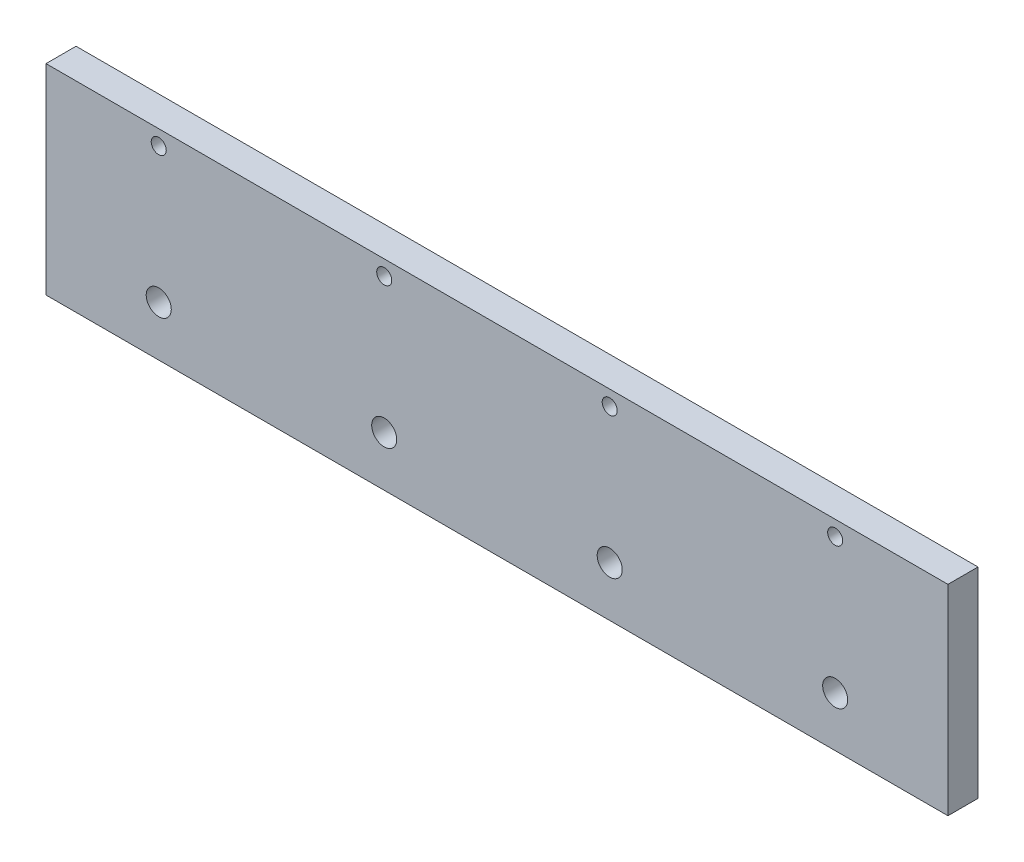
SolidWorks part; units mm, degrees
material "Beech"
ref_plane "Front Plane" through (0, 0, 0) normal (0, 0, 1) x (1, 0, 0)
ref_plane "Top Plane" through (0, 0, 0) normal (0, 1, 0) x (1, 0, 0)
ref_plane "Right Plane" through (0, 0, 0) normal (1, 0, 0) x (0, 0, -1)
sketch "Sketch1" plane through (0, 0, 0) normal (0, 0, 1) x (1, 0, 0)
  line L1 (-180, -40) -> (180, -40)
  line L2 (-180, -40) -> (-180, 40)
  line L3 (-180, 40) -> (180, 40)
  line L4 (180, -40) -> (180, 40)
  line L5 (-180, -40) -> (180, 40) construction
  line L6 (-180, 40) -> (180, -40) construction
  point P0 (0, 0)
extrude "Boss-Extrude1" add sketch "Sketch1" along normal blind 12
sketch "Sketch2" plane through (0, 0, 12) normal (0, 0, 1) x (1, 0, 0)
  line L0 (-180, 40) -> (-180, -40) construction
  line L1 (180, 40) -> (-180, 40) construction
  line L2 (-180, -40) -> (180, -40) construction
  circle A0 centre (-135, 34) radius 3
  circle A1 centre (-135, -20) radius 5
  dimension "D1" = 6
  dimension "D2" = 45
  dimension "D3" = 6
  dimension "D4" = 10
  dimension "D5" = 45
  dimension "D6" = 20
extrude "Cut-Extrude1" cut sketch "Sketch2" against normal up to next
pattern_linear "LPattern1" count 4 spacing 90 along (1, 0, 0) of "Cut-Extrude1"
